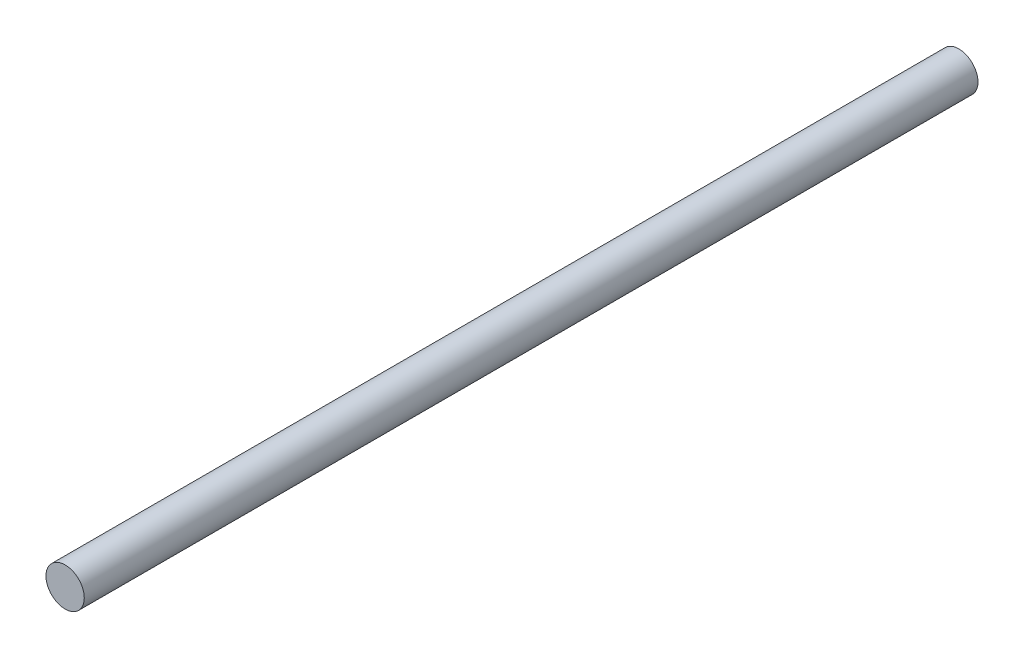
SolidWorks part; units mm, degrees
material "Plain Carbon Steel"
ref_plane "Front Plane" through (0, 0, 0) normal (0, 0, 1) x (1, 0, 0)
ref_plane "Top Plane" through (0, 0, 0) normal (0, 1, 0) x (1, 0, 0)
ref_plane "Right Plane" through (0, 0, 0) normal (1, 0, 0) x (0, 0, -1)
sketch "Sketch1" plane through (0, 0, 0) normal (0, 0, 1) x (1, 0, 0)
  circle A0 centre (0, 0) radius 3.81
  dimension "D1" = 7.62
extrude "Boss-Extrude1" add sketch "Sketch1" along normal blind 177.8
